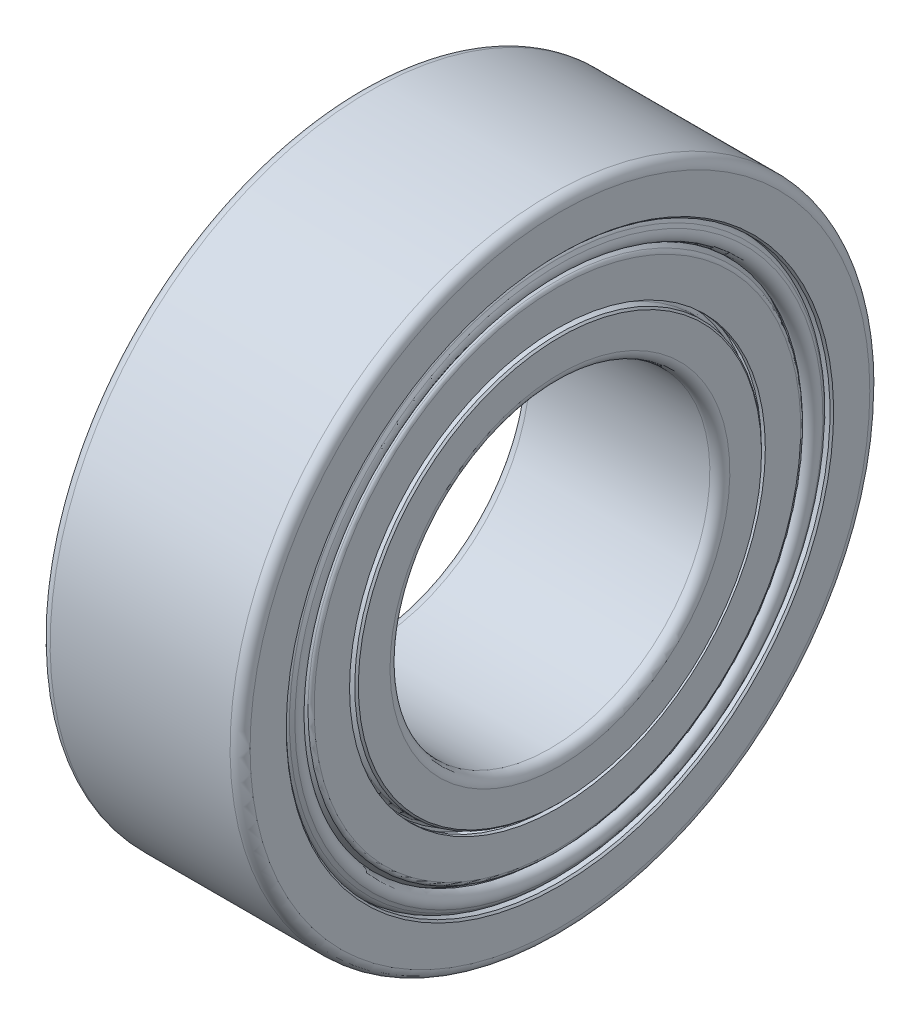
SolidWorks part; units mm, degrees
ref_plane "Front Plane" through (0, 0, 0) normal (0, 0, 1) x (1, 0, 0)
ref_plane "Top Plane" through (0, 0, 0) normal (0, 1, 0) x (1, 0, 0)
ref_plane "Right Plane" through (0, 0, 0) normal (1, 0, 0) x (0, 0, -1)
sketch "Sketch1" plane through (0, 0, 0) normal (1, 0, 0) x (0, 0, -1)
  line L0 (0, 8) -> (0, 7.75) construction
  line L1 (0, 4) -> (0, 4.25) construction
  circle A0 centre (0, 0) radius 8
  circle A1 centre (0, 0) radius 4
  circle A2 centre (0, 0) radius 6.8 construction
  circle A3 centre (0, 0) radius 5.2 construction
  dimension "OD" = 16
  dimension "ID" = 8
  dimension "Outer Ring ID" = 13.6
  dimension "Inner Ring OD" = 10.4
  dimension "Radius" = 0.25
sketch "Sketch2" plane through (0, 0, 0) normal (0, 0, 1) x (1, 0, 0)
  line L0 (-2.5, 8) -> (2.5, 8) construction
  point P3 (0, 8)
  dimension "Width" = 5
sketch "Sketch3" plane through (0, 0, 0) normal (0, 0, 1) x (1, 0, 0)
  line L0 (-2.25, 8) -> (2.25, 8)
  line L1 (-2.5, 7.75) -> (-2.5, 6.845)
  line L2 (2.5, 7.75) -> (2.5, 6.845)
  line L3 (-2.455, 6.8) -> (-2.125, 6.8)
  line L4 (-2.455, 5.0868) -> (-2.5, 5.0418)
  line L5 (-2.2363, 5.0868) -> (-2.455, 5.0868)
  line L6 (2.5, 6.845) -> (2.455, 6.8)
  line L7 (0, 8) -> (0, 6.8) construction
  line L8 (-2.5, 6.845) -> (-2.455, 6.8)
  line L9 (2.455, 5.0868) -> (2.455, 5.2) construction
  line L10 (-2.0781, 5.2) -> (-2.0781, 5.272)
  line L11 (-2.25, 4) -> (2.25, 4)
  line L12 (-2.5, 4.25) -> (-2.5, 5.0418)
  line L13 (2.5, 4.25) -> (2.5, 5.0418)
  line L14 (-2.0781, 5.2) -> (2.0781, 5.2) construction
  line L15 (2.0781, 5.2) -> (2.0781, 4.8833) construction
  line L16 (2.0781, 4.8833) -> (2.0781, 4.5667) construction
  line L17 (2.0781, 5.2) -> (2.0781, 5.0868) construction
  line L18 (2.0781, 5.0868) -> (2.455, 5.0868) construction
  line L19 (2.455, 5.0868) -> (2.5, 5.0418)
  line L20 (2.2363, 5.0868) -> (2.455, 5.0868)
  line L21 (2.0781, 4.5667) -> (2.0781, 4.25) construction
  line L22 (-2.25, 0) -> (2.25, 0) construction
  line L23 (2.125, 6.8) -> (2.125, 6.872)
  line L24 (2.125, 6.872) -> (-2.125, 6.872)
  line L25 (-2.125, 6.8) -> (-2.125, 6.872)
  line L26 (2.125, 6.8) -> (2.455, 6.8)
  line L27 (-2.0781, 5.272) -> (2.0781, 5.272)
  line L28 (2.0781, 5.272) -> (2.0781, 5.2)
  arc A0 (-2.5, 7.75) -> (-2.25, 8) centre (-2.25, 7.75) cw
  arc A1 (2.25, 8) -> (2.5, 7.75) centre (2.25, 7.75) cw
  arc A2 (-2.5, 4.25) -> (-2.25, 4) centre (-2.25, 4.25) ccw
  arc A3 (2.25, 4) -> (2.5, 4.25) centre (2.25, 4.25) ccw
  arc A4 (2.0781, 5.2) -> (2.2363, 5.0868) centre (2.2363, 5.2539) ccw
  arc A5 (-2.0781, 5.2) -> (-2.2363, 5.0868) centre (-2.2363, 5.2539) cw
  point P7 (-2.5, 8)
  point P15 (2.5, 8)
  point P30 (0, 5.2)
  point P48 (0, 6.872)
  dimension "D1" = 0.25
  dimension "D4" = 0.25
  dimension "D2" = 135
  dimension "D3" = 0.045
  dimension "D5" = 135
  dimension "D7" = 0.4219
  dimension "D9" = 0.072
  dimension "D10" = 0.375
  dimension "D8" = 0.1582
  dimension "D6" = 0.1582
revolve "Revolve1" add sketch "Sketch3" angle 360 about L22
sketch "Sketch4" plane through (0, 0, 0) normal (0, 0, 1) x (1, 0, 0)
  line L6 (2.2242, 6.3895) -> (2.1767, 6.4169) construction
  line L7 (2.1142, 6.58) -> (2.1142, 6.3519)
  line L8 (2.1267, 6.3303) -> (2.3813, 6.1833)
  line L9 (2.4375, 6.0859) -> (2.4375, 5.2)
  line L10 (2.5, -7.75) -> (2.5, 7.75) construction
  line L11 (2.4375, 5.2) -> (2.3375, 5.2) construction
  line L12 (2.4042, 6.4934) -> (2.4375, 6.4934) construction
  line L15 (2.1767, 6.4169) -> (2.1267, 6.3303) construction
  line L18 (2.3381, 6.64) -> (2.3881, 6.5534)
  line L20 (2.125, 6.8) -> (2.455, 6.8) construction
  arc A0 (2.1142, 6.58) -> (2.3381, 6.64) centre (2.2342, 6.58) cw
  arc A1 (2.3881, 6.5534) -> (2.2242, 6.3895) centre (2.2842, 6.4934) cw construction
  arc A2 (2.3813, 6.1833) -> (2.4375, 6.0859) centre (2.325, 6.0859) cw
  arc A3 (2.1142, 6.3519) -> (2.1267, 6.3303) centre (2.1392, 6.3519) ccw
  arc A4 (2.3881, 6.5534) -> (2.2842, 6.3734) centre (2.2842, 6.4934) cw
  point P18 (2.0781, 5.2)
  point P28 (2.4375, 6.1508)
  point P31 (2.1142, 6.3375)
  dimension "D8" = 0.1125
  dimension "D9" = 0.025
  dimension "D6" = 0.12
  dimension "D1" = 0.0625
  dimension "D3" = 0.1
  dimension "D2" = 0.1
  dimension "D7" = 30
  dimension "D4" = 120
  dimension "D12" = 0.0333
  dimension "D5" = 0.1
revolve "Revolve-Thin1" add sketch "Sketch4" angle 360 about L22
mirror "Mirror2" about plane through (0, 0, 0) normal (1, 0, 0) of bodies 106
delete or keep bodies "Body-Delete/Keep 1" type delete bodies bodies 113
mirror "Mirror1" about plane through (0, 0, 0) normal (1, 0, 0) of bodies 106 112
equation "\"D4@Sketch3\"=\"D1@Sketch3\""
equation "\"D1@Sketch3\"=\"Radius@Sketch1\""
equation "\"D8@Sketch4\"=\"D3@Sketch4\"*1.125"
equation "\"D9@Sketch4\"=\"D3@Sketch4\"*.25"
equation "\"Outer Ring ID@Sketch1\"=\"OD@Sketch1\"-(((\"OD@Sketch1\"-\"ID@Sketch1\")/2)*.3*2)"
equation "\"Inner Ring OD@Sketch1\"=\"ID@Sketch1\"+(((\"OD@Sketch1\"-\"ID@Sketch1\")/2)*.3*2)"
equation "\"Radius@Sketch1\"=\"Width@Sketch2\"*.05"
equation "\"D3@Sketch4\"=\"Width@Sketch2\"*.02"
equation "\"D2@Sketch4\"=\"D3@Sketch4\""
equation "\"D12@Sketch4\"=\"D3@Sketch4\"/3"
equation "\"D6@Sketch4\"=((\"Outer Ring ID@Sketch1\"-\"Inner Ring OD@Sketch1\")/2)*.075"
equation "\"D10@Sketch3\"=\"Width@Sketch2\"*.075"
equation "\"D9@Sketch3\"=((\"OD@Sketch1\"-\"Outer Ring ID@Sketch1\")/2)*.06"
equation "\"D3@Sketch3\"=\"D9@Sketch3\"*.625"
equation "\"D7@Sketch3\"=\"D10@Sketch3\"*1.125"
equation "\"D6@Sketch3\"=\"D7@Sketch3\"*.375"
equation "\"D8@Sketch3\"=\"D6@Sketch3\""
equation "\"D1@Sketch4\"=\"D3@Sketch4\"*.625"
equation "\"D5@Sketch4\"=((\"Outer Ring ID@Sketch1\"-\"Inner Ring OD@Sketch1\")/2)*.0625"
equation "\"D3@Revolve-Thin1\"=\"D5@Sketch4\""
